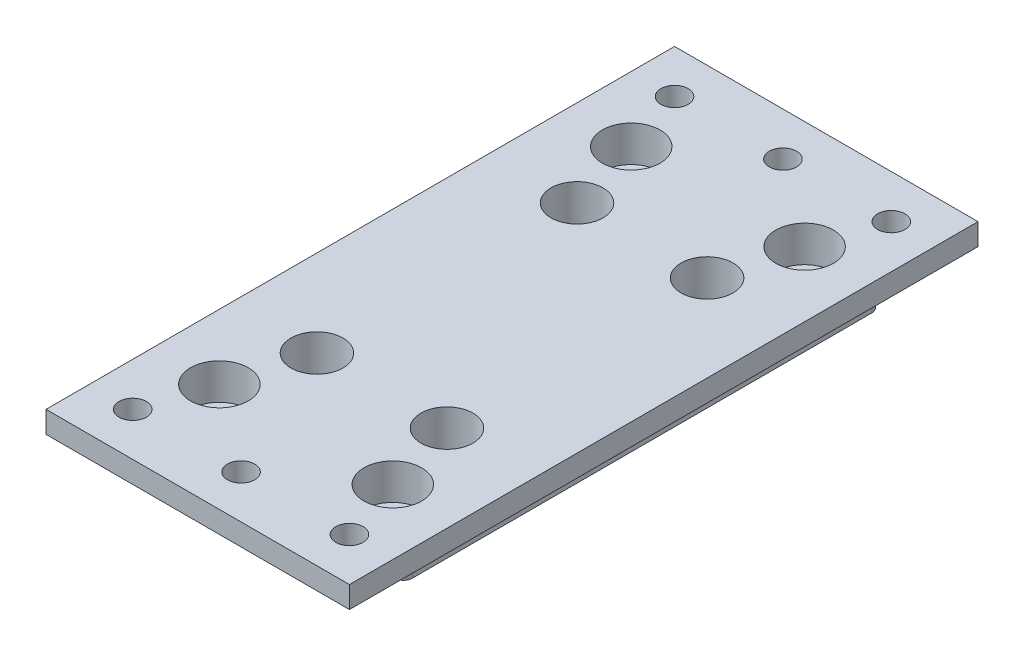
SolidWorks part; units mm, degrees
ref_plane "前视基准面" through (0, 0, 0) normal (0, 0, 1) x (1, 0, 0)
ref_plane "上视基准面" through (0, 0, 0) normal (0, 1, 0) x (1, 0, 0)
ref_plane "右视基准面" through (0, 0, 0) normal (1, 0, 0) x (0, 0, -1)
other "Configuration Table"
sketch "草图1" plane through (0, 0, 0) normal (0, 1, 0) x (1, 0, 0)
  line L0 (0, 63.3985) -> (0, -70.8925) construction
  line L1 (-28, -55) -> (28, -55)
  line L2 (-30, -53) -> (-30, 53)
  line L3 (-28, 55) -> (28, 55)
  line L4 (30, -53) -> (30, 53)
  line L5 (-30, -55) -> (30, 55) construction
  line L6 (-30, 55) -> (30, -55) construction
  line L7 (-53.0107, 0) -> (66.4937, 0) construction
  circle A0 centre (-20, 47.5) radius 4.1
  circle A1 centre (20, 47.5) radius 4.1
  circle A2 centre (-20, -47.5) radius 4.1
  circle A3 centre (20, -47.5) radius 4.1
  arc A4 (-30, 53) -> (-28, 55) centre (-28, 53) cw
  arc A5 (30, 53) -> (28, 55) centre (28, 53) ccw
  arc A6 (28, -55) -> (30, -53) centre (28, -53) ccw
  arc A7 (-28, -55) -> (-30, -53) centre (-28, -53) cw
  circle A8 centre (-15, 30) radius 6
  circle A9 centre (15, 30) radius 6
  circle A10 centre (15, -30) radius 6
  circle A11 centre (-15, -30) radius 6
  point P0 (0, 0)
  dimension "D3" = 8.2
  dimension "D6" = 2
  dimension "D9" = 12
  dimension "D1" = 110
  dimension "D2" = 60
  dimension "D4" = 20
  dimension "D5" = 47.5
  dimension "D7" = 15
  dimension "D8" = 25
extrude "凸台-拉伸1" add sketch "草图1" along normal blind 11
sketch "草图2" plane through (0, 11, 0) normal (0, 1, 0) x (1, 0, 0)
  line L0 (0, 57.2896) -> (0, -61.8323) construction
  line L1 (-46.4374, 0) -> (48.9611, 0) construction
  circle A0 centre (-20, 47.5) radius 6.65
  circle A1 centre (-20, -47.5) radius 6.65
  circle A2 centre (20, 47.5) radius 6.65
  circle A3 centre (20, -47.5) radius 6.65
  dimension "D1" = 13.3
extrude "切除-拉伸1" cut sketch "草图2" against normal blind 8.3
sketch "草图3" plane through (0, 0, 0) normal (0, -1, 0) x (1, 0, 0)
  line L2 (0, -73.0044) -> (0, 60.7934) construction
  line L3 (-85.6515, 0) -> (93.5014, 0) construction
  line L5 (35, 72.5) -> (-35, 72.5)
  line L6 (35, 72.5) -> (35, -72.5)
  line L7 (35, -72.5) -> (-35, -72.5)
  line L8 (-35, 72.5) -> (-35, -72.5)
  line L9 (35, 72.5) -> (-35, -72.5) construction
  line L10 (35, -72.5) -> (-35, 72.5) construction
  line L14 (-30, 53) -> (-30, -53)
  line L15 (28, 55) -> (-28, 55)
  line L16 (30, -53) -> (30, 53)
  line L17 (-28, -55) -> (28, -55)
  line L18 (-30, 53) -> (-30, -53)
  line L19 (28, 55) -> (-28, 55)
  line L20 (30, -53) -> (30, 53)
  line L21 (-28, -55) -> (28, -55)
  circle A0 centre (-25, 62.5) radius 3.15
  circle A1 centre (25, 62.5) radius 3.15
  circle A2 centre (25, -62.5) radius 3.15
  circle A3 centre (-25, -62.5) radius 3.15
  circle A4 centre (0, 62.5) radius 3.15
  circle A5 centre (0, -62.5) radius 3.15
  arc A14 (-30, -53) -> (-28, -55) centre (-28, -53) ccw
  arc A15 (-28, 55) -> (-30, 53) centre (-28, 53) ccw
  arc A16 (30, 53) -> (28, 55) centre (28, 53) ccw
  arc A17 (28, -55) -> (30, -53) centre (28, -53) ccw
  arc A18 (-30, -53) -> (-28, -55) centre (-28, -53) ccw
  arc A19 (-28, 55) -> (-30, 53) centre (-28, 53) ccw
  arc A20 (30, 53) -> (28, 55) centre (28, 53) ccw
  arc A21 (28, -55) -> (30, -53) centre (28, -53) ccw
  point P17 (0, 0)
  dimension "D1" = 6.3
  dimension "D4" = 6.3
  dimension "D6" = 10
  dimension "D2" = 62.5
  dimension "D3" = 25
  dimension "D5" = 25
  dimension "D7" = 10
  dimension "D8" = 0
extrude "凸台-拉伸2" add sketch "草图3" along normal blind 5 from surface at -11 starting at face at (-20, 11, 40.85)
